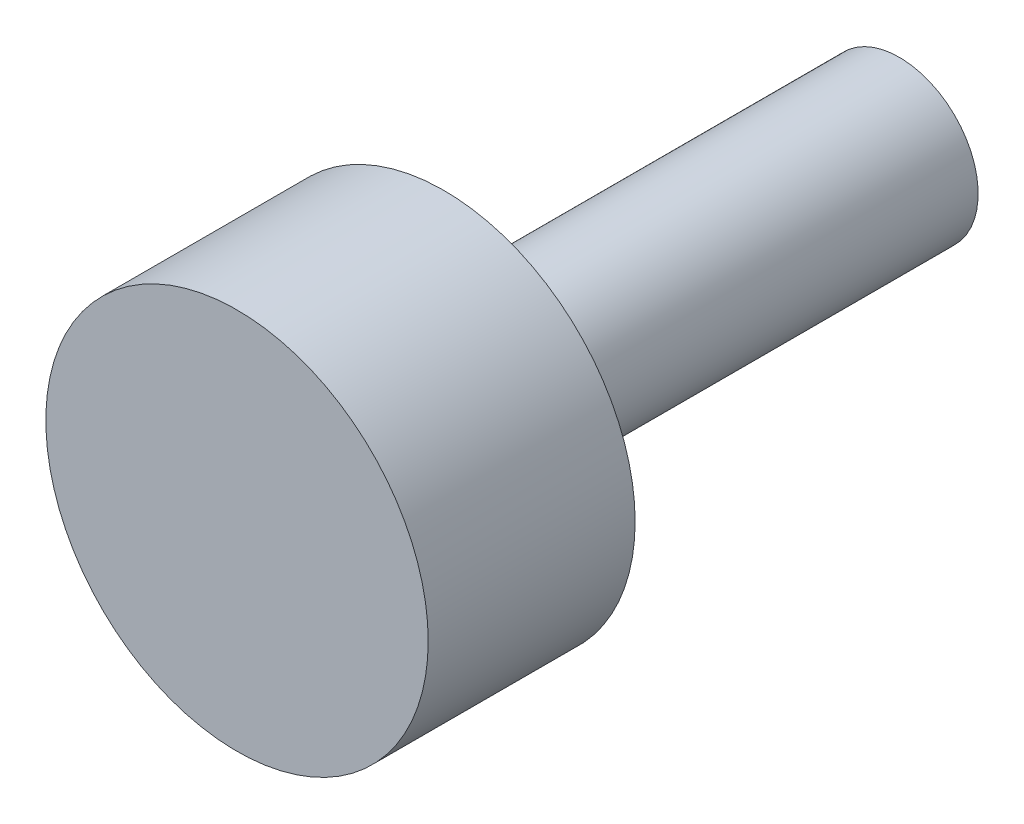
SolidWorks part; units mm, degrees
ref_plane "前基準面" through (0, 0, 0) normal (0, 0, 1) x (1, 0, 0)
ref_plane "上基準面" through (0, 0, 0) normal (0, 1, 0) x (1, 0, 0)
ref_plane "右基準面" through (0, 0, 0) normal (1, 0, 0) x (0, 0, -1)
sketch "草圖1" plane through (0, 0, 0) normal (0, 0, 1) x (1, 0, 0)
  line L0 (-53.1655, -91.0074) -> (-53.1655, -49.1237) construction
  line L1 (-50.0655, -91.7074) -> (-52.4655, -91.7074) construction
  circle A0 centre (-43.1655, -81.7074) radius 8.5
  point P7 (-51.2655, -91.7074)
  dimension "D1" = 17
  dimension "D2" = 10
  dimension "D3" = 10
extrude "填料-伸長1" add sketch "草圖1" along normal blind 9.2 contours A0
sketch "草圖2" plane through (0, 0, 0) normal (0, 0, -1) x (-1, 0, 0)
  circle A0 centre (43.1655, -81.7074) radius 3.5
  circle A1 centre (43.1655, -81.7074) radius 8.5 construction
  dimension "D1" = 7
  dimension "D2" = 0
extrude "填料-伸長2" add sketch "草圖2" along normal blind 20.25
